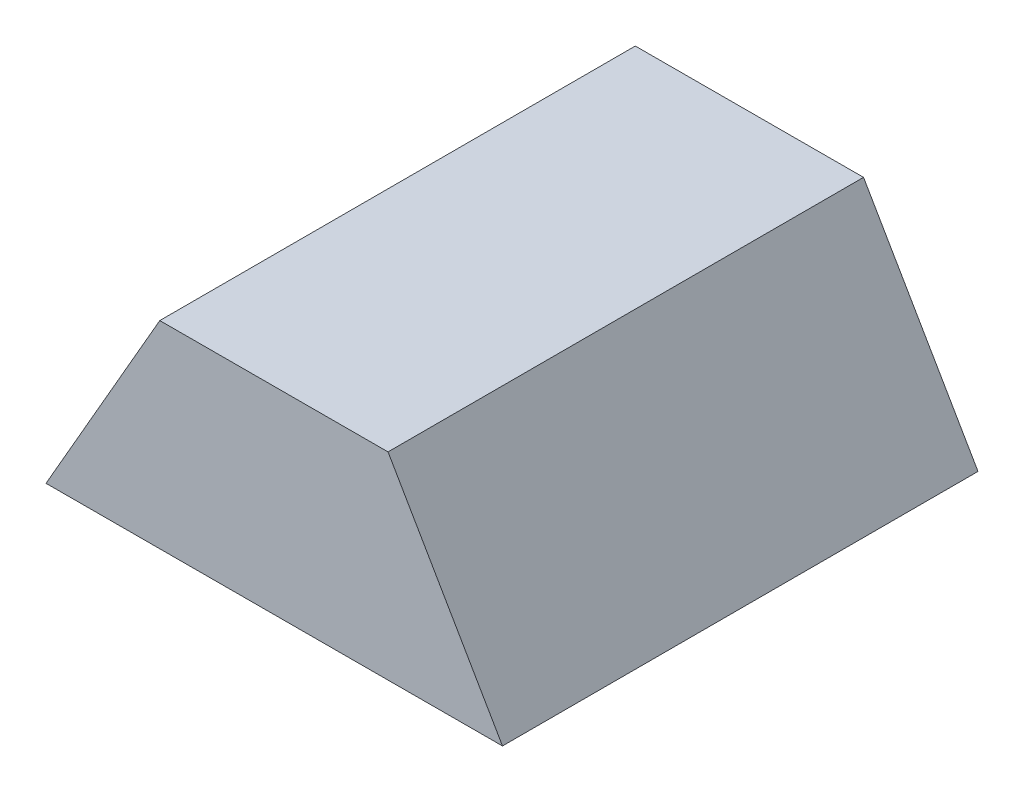
SolidWorks part; units mm, degrees
ref_plane "Alzado" through (0, 0, 0) normal (0, 0, 1) x (1, 0, 0)
ref_plane "Planta" through (0, 0, 0) normal (0, 1, 0) x (1, 0, 0)
ref_plane "Vista lateral" through (0, 0, 0) normal (1, 0, 0) x (0, 0, -1)
sketch "Croquis2" plane through (0, 0, 0) normal (0, 0, 1) x (1, 0, 0)
  line L0 (-24, -0.0411) -> (24, 0.0411)
  line L2 (24, 0.0411) -> (11.9644, 20.8052)
  line L3 (11.9644, 20.8052) -> (-12.0356, 20.764)
  line L4 (-12.0356, 20.764) -> (-24, -0.0411)
  line L7 (-24, -0.0411) -> (-17.9822, -10.4231) [skipped]
  line L8 (12.0356, -20.764) -> (18.0178, -10.3615) [skipped]
  line L9 (0.0356, -20.7846) -> (12.0356, -20.764) [skipped]
  arc A1 (17.9822, 10.4231) -> (-18.0178, 10.3615) centre (0, 0) ccw construction
  dimension "D1" = 48
extrude "Saliente-Extruir1" add sketch "Croquis2" along normal blind 50
sketch "Croquis3" plane through (0, 0, 0) normal (0, 0, -1) x (-1, 0, 0)
  circle A0 centre (0, 9.933) radius 5
  dimension "D1" = 10
extrude "Cortar-Extruir1" cut sketch "Croquis3" against normal blind 10
